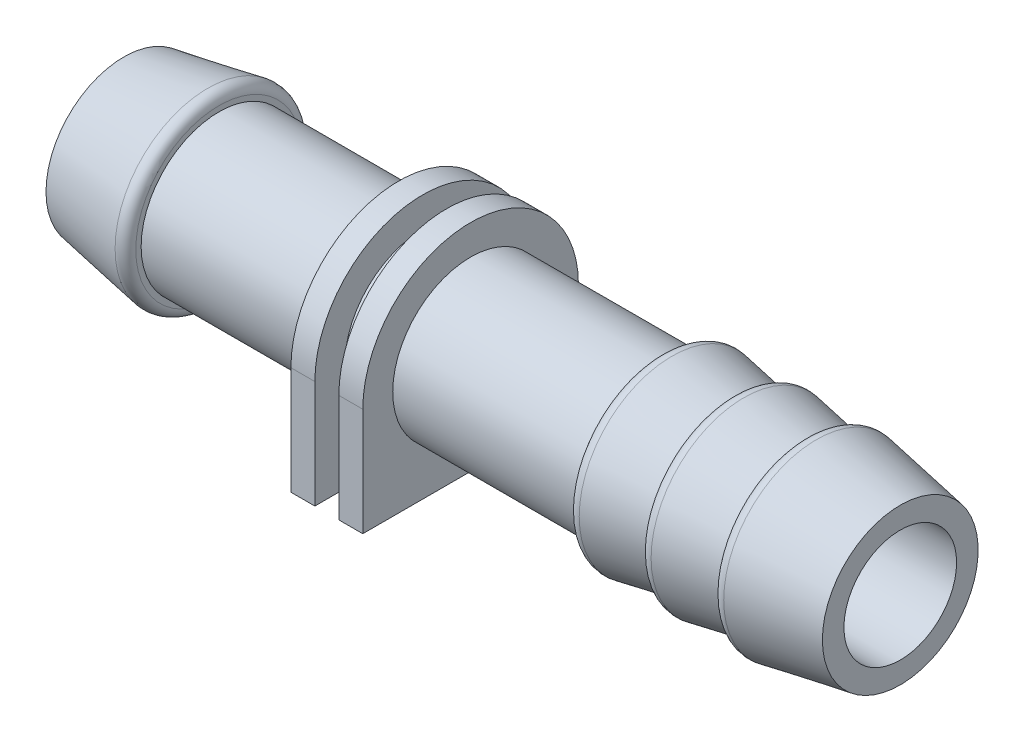
SolidWorks part; units mm, degrees
ref_plane "Front Plane" through (0, 0, 0) normal (0, 0, 1) x (1, 0, 0)
ref_plane "Top Plane" through (0, 0, 0) normal (0, 1, 0) x (1, 0, 0)
ref_plane "Right Plane" through (0, 0, 0) normal (1, 0, 0) x (0, 0, -1)
sketch "Sketch1" plane through (0, 0, 0) normal (0, 1, 0) x (1, 0, 0)
  line L0 (-25.4239, 0) -> (17.3627, 0) construction
  line L1 (-18.9129, 0) -> (13.4871, 0)
  line L2 (-18.9129, -3.25) -> (-18.9129, 0)
  line L3 (13.4871, -3.25) -> (13.4871, 0)
  line L4 (-14.943, -3.25) -> (3.4871, -3.25)
  line L5 (13.4871, -3.25) -> (9.9866, -3.8672)
  line L6 (9.5172, -3.4733) -> (9.5172, -3.4157)
  line L7 (3.4871, -3.25) -> (3.4871, -3.4733)
  line L8 (3.9565, -3.8672) -> (6.4871, -3.421)
  line L9 (6.4871, -3.4733) -> (6.4871, -3.421)
  line L10 (6.9565, -3.8672) -> (9.5172, -3.4157)
  line L11 (-18.9129, -3.25) -> (-15.4125, -3.8672)
  line L12 (-14.943, -3.4733) -> (-14.943, -3.25)
  arc A0 (9.9866, -3.8672) -> (9.5172, -3.4733) centre (9.9172, -3.4733) cw
  arc A1 (6.9565, -3.8672) -> (6.4871, -3.4733) centre (6.8871, -3.4733) cw
  arc A2 (3.9565, -3.8672) -> (3.4871, -3.4733) centre (3.8871, -3.4733) cw
  arc A3 (-14.943, -3.4733) -> (-15.4125, -3.8672) centre (-15.343, -3.4733) cw
  dimension "D1" = 0.4
  dimension "D3" = 3.25
  dimension "D4" = 10
  dimension "D5" = 10
  dimension "D6" = 10
  dimension "D7" = 3
  dimension "D8" = 10
revolve "Revolve1" add sketch "Sketch1" angle 360 about L0
ref_plane "Plane1" through (-7.443, 0, 0) normal (1, 0, 0) x (0, 0, -1)
sketch "Sketch3" plane through (-7.443, 0, 0) normal (1, 0, 0) x (0, 0, -1)
  line L0 (4.5, -4.5) -> (-4.5, -4.5)
  line L1 (-4.5, -4.5) -> (-4.5, 0)
  line L2 (4.5, 0) -> (4.5, -4.5)
  arc A0 (4.5, 0) -> (-4.5, 0) centre (0, 0) ccw
  dimension "D1" = 9
extrude "Boss-Extrude1" add sketch "Sketch3" along normal blind 1
sketch "Sketch2" plane through (13.4871, 0, 0) normal (1, 0, 0) x (0, 0, -1)
  circle A0 centre (0, 0) radius 2.35
  dimension "D1" = 4.7
extrude "Cut-Extrude1" cut sketch "Sketch2" against normal up to surface (32.4 mm away) up to face at (-18.9129, 0, 3.25)
pattern_linear "LPattern1" count 2 spacing 2 along (1, 0, 0) of "Boss-Extrude1"
